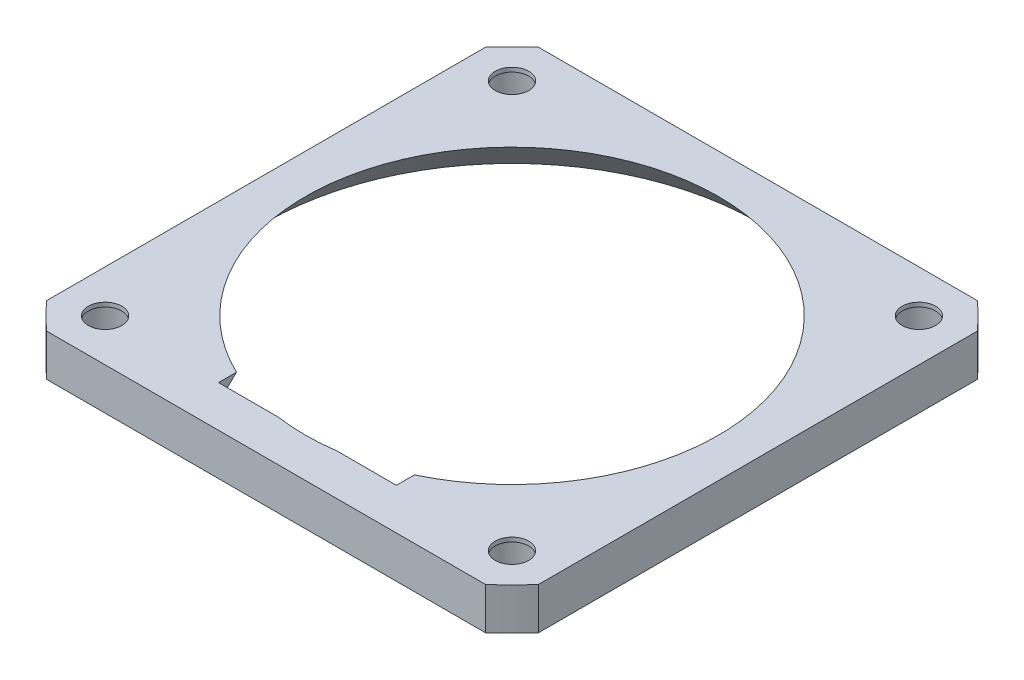
SolidWorks part; units mm, degrees
material "PET 90%"
ref_plane "Front Plane" through (0, 0, 0) normal (0, 0, 1) x (1, 0, 0)
ref_plane "Top Plane" through (0, 0, 0) normal (0, 1, 0) x (1, 0, 0)
ref_plane "Right Plane" through (0, 0, 0) normal (1, 0, 0) x (0, 0, -1)
sketch "Sketch1" plane through (0, 0, 0) normal (0, 1, 0) x (1, 0, 0)
  line L0 (0, 0) -> (13.9657, 13.9657) construction
  line L1 (13.9657, 13.9657) -> (19.4454, 19.4454) construction
  line L2 (19.4454, 19.4454) -> (22.2739, 22.2739) construction
  circle A0 centre (-19.4454, -19.4454) radius 1.6 construction
  circle A1 centre (-19.4454, -19.4454) radius 1.6
  circle A2 centre (-19.4454, 19.4454) radius 1.6 construction
  circle A3 centre (-19.4454, 19.4454) radius 1.6
  circle A4 centre (19.4454, -19.4454) radius 1.6 construction
  circle A5 centre (19.4454, -19.4454) radius 1.6
  circle A6 centre (19.4454, 19.4454) radius 1.6 construction
  circle A7 centre (19.4454, 19.4454) radius 1.6
  circle A8 centre (0, 0) radius 16.7505 construction
  circle A9 centre (0, 0) radius 16.7505 construction
  circle A10 centre (0, 0) radius 19.7505 construction
  circle A11 centre (0, 0) radius 31.5
  dimension "D2" = 3
  dimension "D1" = 4
extrude "Base" add sketch "Sketch1" against normal blind 4
sketch "Sketch3" plane through (0, -4, 0) normal (0, -1, 0) x (-1, 0, 0)
  line L4 (-13.9657, 13.9657) -> (-19.4454, 19.4454) construction
  line L5 (-16.617, 16.617) -> (-17.3241, 17.3241) construction
  circle A0 centre (0, 0) radius 23.5
  circle A7 centre (-19.4454, 19.4454) radius 3 construction
  circle A8 centre (19.4454, 19.4454) radius 3 construction
  circle A9 centre (19.4454, -19.4454) radius 3 construction
  circle A10 centre (-19.4454, -19.4454) radius 3 construction
  dimension "D1" = 1
  dimension "D2" = 6
sketch "Sketch4" plane through (0, 0, 0) normal (0, 1, 0) x (1, 0, 0)
  line L0 (0, 0) -> (-31.5, 0) construction
  circle A0 centre (0, 0) radius 19.7505 construction
  circle A1 centre (0, 0) radius 19.7505
  circle A2 centre (0, 0) radius 31.5 construction
ref_plane "Plane2" through (0, -4, 0) normal (0, -1, 0) x (-1, 0, 0)
loft "Skirt" cut profiles "Sketch3", "Sketch4"
sketch "Sketch6" plane through (0, -4, 0) normal (0, -1, 0) x (-1, 0, 0)
  line L0 (20.9762, 23.5) -> (-20.9762, 23.5)
  line L1 (20.9762, -23.5) -> (-20.9762, -23.5)
  line L2 (23.5, -20.9762) -> (23.5, 20.9762)
  line L3 (-23.5, -20.9762) -> (-23.5, 20.9762)
  circle A0 centre (0, 0) radius 31.5 construction
  circle A3 centre (0, 0) radius 23.5 construction
  circle A4 centre (0, 0) radius 31.5 construction
  arc A5 (23.5, -20.9762) -> (23.5, 20.9762) centre (0, 0) ccw
  arc A6 (20.9762, 23.5) -> (-20.9762, 23.5) centre (0, 0) ccw
  arc A7 (-23.5, 20.9762) -> (-23.5, -20.9762) centre (0, 0) ccw
  arc A8 (-20.9762, -23.5) -> (20.9762, -23.5) centre (0, 0) ccw
extrude "Connectors" cut sketch "Sketch6" against normal through all
sketch "Sketch5" plane through (0, -4, 0) normal (0, -1, 0) x (-1, 0, 0)
  circle A4 centre (19.4454, -19.4454) radius 3 construction
  circle A5 centre (19.4454, -19.4454) radius 3
  circle A6 centre (19.4454, 19.4454) radius 3 construction
  circle A7 centre (19.4454, 19.4454) radius 3
  circle A8 centre (-19.4454, -19.4454) radius 3 construction
  circle A9 centre (-19.4454, -19.4454) radius 3
  circle A10 centre (-19.4454, 19.4454) radius 3 construction
  circle A11 centre (-19.4454, 19.4454) radius 3
extrude "Screw heads" cut sketch "Sketch5" against normal offset from surface (3.6 mm away) 0.4 up to face at (0, 0, 0)
sketch "Sketch7" plane through (0, 0, 0) normal (0, 1, 0) x (1, 0, 0)
  line L0 (8.5, -18.7505) -> (-8.5, -18.7505) construction
  line L1 (8.5, -18.7505) -> (-8.5, -18.7505) construction
  line L2 (-8.5, -19.5505) -> (8.5, -19.5505) construction
  line L3 (-8.5, -19.5505) -> (8.5, -19.5505)
  line L4 (-8.5, -18.7505) -> (-8.5, -19.5505) construction
  line L5 (-8.5, -18.7505) -> (-8.5, -19.5505)
  line L6 (8.5, -19.5505) -> (8.5, -18.7505) construction
  line L7 (8.5, -19.5505) -> (8.5, -18.7505)
  line L8 (-8.5, -18.7505) -> (-8.5, 0)
  line L9 (-8.5, 0) -> (0, 0)
  line L10 (0, 0) -> (8.5, 0)
  line L11 (8.5, 0) -> (8.5, -18.7505)
extrude "Flex cable" cut sketch "Sketch7" against normal through all
